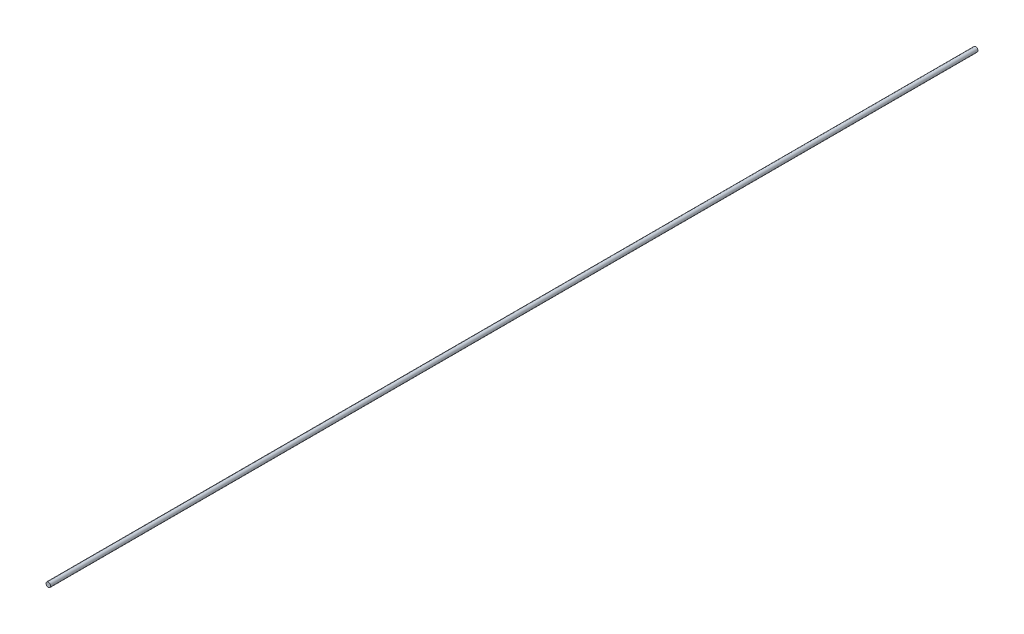
SolidWorks part; units mm, degrees
ref_plane "Front Plane" through (0, 0, 0) normal (0, 0, 1) x (1, 0, 0)
ref_plane "Top Plane" through (0, 0, 0) normal (0, 1, 0) x (1, 0, 0)
ref_plane "Right Plane" through (0, 0, 0) normal (1, 0, 0) x (0, 0, -1)
sketch "Sketch1" plane through (0, 0, 0) normal (0, 0, 1) x (1, 0, 0)
  circle A0 centre (0, 0) radius 0.5
  dimension "D1" = 1
extrude "Boss-Extrude1" add sketch "Sketch1" along normal blind 200
